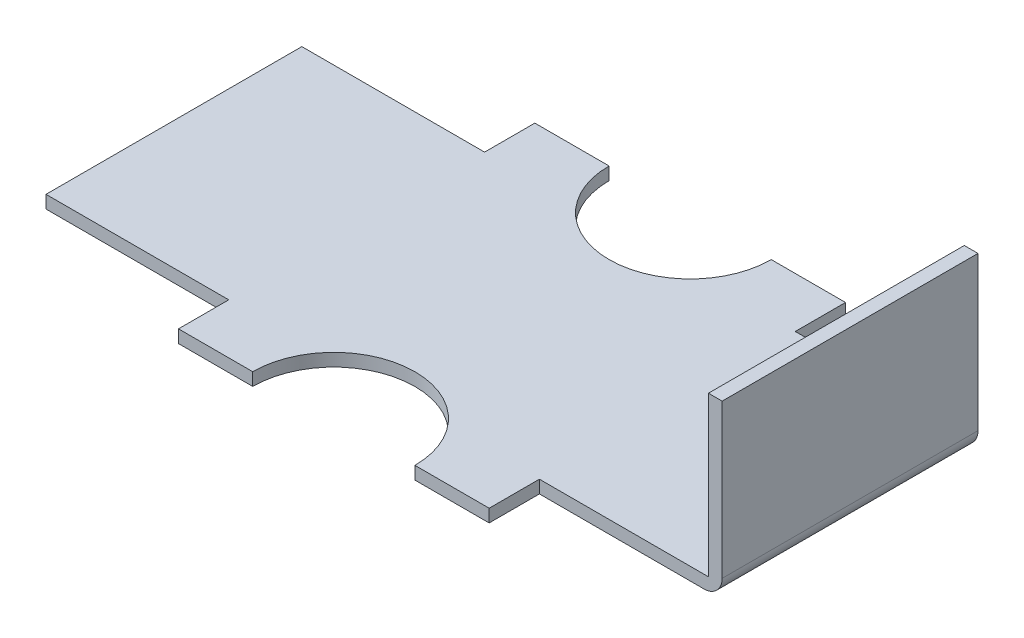
SolidWorks part; units mm, degrees
ref_plane "Front Plane" through (0, 0, 0) normal (0, 0, 1) x (1, 0, 0)
ref_plane "Top Plane" through (0, 0, 0) normal (0, 1, 0) x (1, 0, 0)
ref_plane "Right Plane" through (0, 0, 0) normal (1, 0, 0) x (0, 0, -1)
sketch "Sketch1" plane through (0, 0, 0) normal (0, 1, 0) x (1, 0, 0)
  line L1 (-9.398, -4.953) -> (9.398, -4.953)
  line L2 (-9.398, -4.953) -> (-9.398, 4.953)
  line L3 (-9.398, 4.953) -> (9.398, 4.953)
  line L4 (9.398, -4.953) -> (9.398, 4.953)
  line L5 (-9.398, -4.953) -> (9.398, 4.953) construction
  line L6 (-9.398, 4.953) -> (9.398, -4.953) construction
  point P0 (0, 0)
  dimension "D1" = 9.906
  dimension "D2" = 18.796
extrude "Boss-Extrude1" add sketch "Sketch1" along normal blind 0.3556
sketch "Sketch2" plane through (0, 0.3556, 0) normal (0, 1, 0) x (1, 0, 0)
  line L0 (9.398, 4.953) -> (-9.398, 4.953) construction
  line L2 (-10.3436, 0) -> (10.3638, 0) construction
  line L3 (-9.398, 4.953) -> (-4.318, 4.953)
  line L4 (-9.398, 4.953) -> (-9.398, 3.556)
  line L5 (-9.398, 3.556) -> (-4.318, 3.556)
  line L6 (-4.318, 4.953) -> (-4.318, 3.556)
  line L11 (-0.1956, 0) -> (0.1956, 0) construction
  line L12 (9.398, -3.556) -> (4.318, -3.556)
  line L13 (9.398, 4.953) -> (4.318, 4.953)
  line L14 (9.398, 4.953) -> (9.398, 3.556)
  line L15 (9.398, 3.556) -> (4.318, 3.556)
  line L16 (4.318, 4.953) -> (4.318, 3.556)
  line L17 (4.318, -4.953) -> (4.318, -3.556)
  line L18 (9.398, -4.953) -> (4.318, -4.953)
  line L19 (9.398, -4.953) -> (9.398, -3.556)
  line L20 (-9.398, -3.556) -> (-4.318, -3.556)
  line L21 (-4.318, -4.953) -> (-4.318, -3.556)
  line L22 (-9.398, -4.953) -> (-4.318, -4.953)
  line L23 (-9.398, -4.953) -> (-9.398, -3.556)
  circle A0 centre (0, 4.953) radius 2.2542
  circle A2 centre (0, -4.953) radius 2.2542
  point P20 (4.318, 4.2545)
  dimension "D1" = 4.5085
  dimension "D2" = 5.08
  dimension "D3" = 1.397
  dimension "D4" = 5.08
  dimension "D5" = 1.397
extrude "Cut-Extrude1" cut sketch "Sketch2" against normal through all
sketch "Sketch3" plane through (0, 0.3556, 0) normal (0, 1, 0) x (1, 0, 0)
  line L0 (9.398, -3.556) -> (4.318, -3.556) construction
  line L1 (9.398, 3.556) -> (9.017, 3.556)
  line L2 (9.398, 3.556) -> (9.398, -3.556)
  line L3 (9.398, -3.556) -> (9.017, -3.556)
  line L4 (9.017, 3.556) -> (9.017, -3.556)
  dimension "D1" = 0.381
extrude "Boss-Extrude2" add sketch "Sketch3" along normal blind 4.4196
fillet "Fillet2" radius 0.508 1 edges at (9.398, 0, 0)
